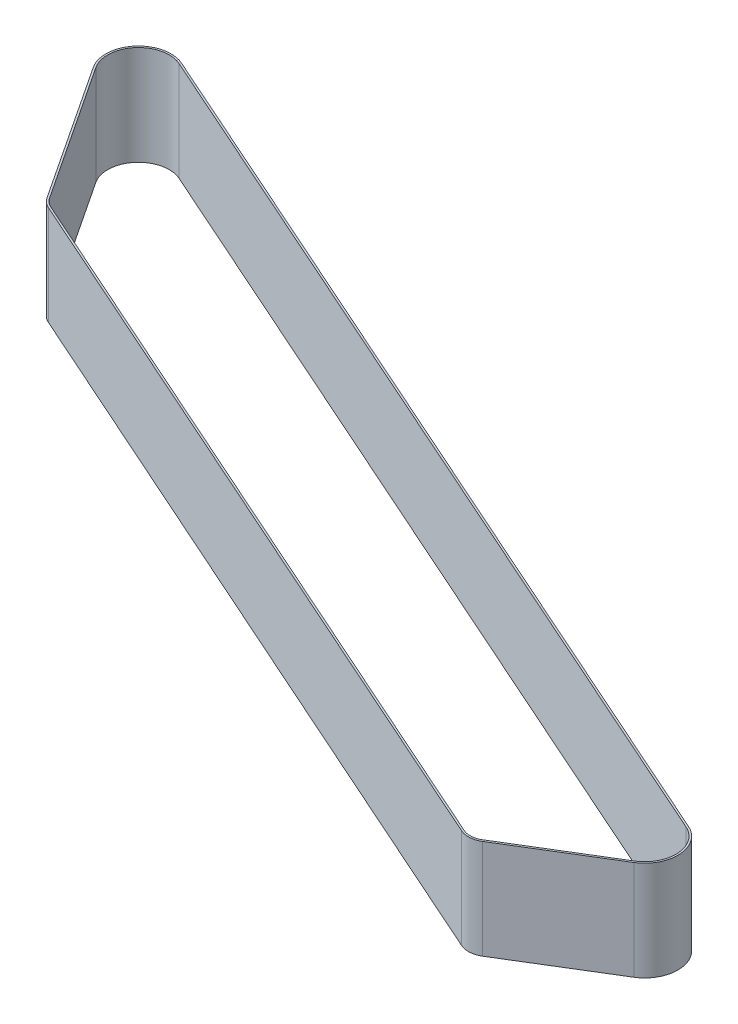
SolidWorks part; units mm, degrees
ref_plane "前视基准面" through (0, 0, 0) normal (0, 0, 1) x (1, 0, 0)
ref_plane "上视基准面" through (0, 0, 0) normal (0, 1, 0) x (1, 0, 0)
ref_plane "右视基准面" through (0, 0, 0) normal (1, 0, 0) x (0, 0, -1)
other "Configuration Table"
sketch "草图1" plane through (0, 0, 0) normal (0, 1, 0) x (1, 0, 0)
  line L0 (-224.4983, 161.4621) -> (272.3929, -59.9766)
  line L9 (274.3399, -90.0088) -> (222.2467, -121.7674)
  line L11 (213.5978, -121.8083) -> (-191.8813, 59.1529)
  line L12 (-245.2439, 136.9944) -> (-196.1969, 62.7099)
  line L13 (-246.0784, 136.4435) -> (-197.1993, 62.4054)
  line L14 (-224.0912, 162.3755) -> (272.7999, -59.0632)
  line L15 (274.8615, -90.862) -> (223.8753, -122.0316)
  line L16 (213.1902, -122.7215) -> (-192.2889, 58.2398)
  arc A0 (-224.4983, 161.4621) -> (-245.2439, 136.9944) centre (-231.2997, 146.2002) ccw
  arc A3 (274.3399, -90.0088) -> (272.3929, -59.9766) centre (265.4729, -75.5045) ccw
  arc A13 (-224.0912, 162.3755) -> (-246.0784, 136.4435) centre (-231.2997, 146.2002) ccw
  arc A14 (213.5978, -121.8083) -> (222.2467, -121.7674) centre (217.877, -112.2199) ccw
  arc A15 (-196.1969, 62.7099) -> (-191.8813, 59.1529) centre (-187.6021, 68.7414) ccw
  arc A16 (274.8615, -90.862) -> (272.7999, -59.0632) centre (265.4729, -75.5045) ccw
  arc A19 (213.1902, -122.7215) -> (225.2797, -121.0204) centre (217.877, -112.2199) ccw
  arc A20 (-197.1993, 62.4054) -> (-192.2889, 58.2398) centre (-187.6021, 68.7414) ccw
extrude "凸台-拉伸1" add sketch "草图1" along normal blind 54
